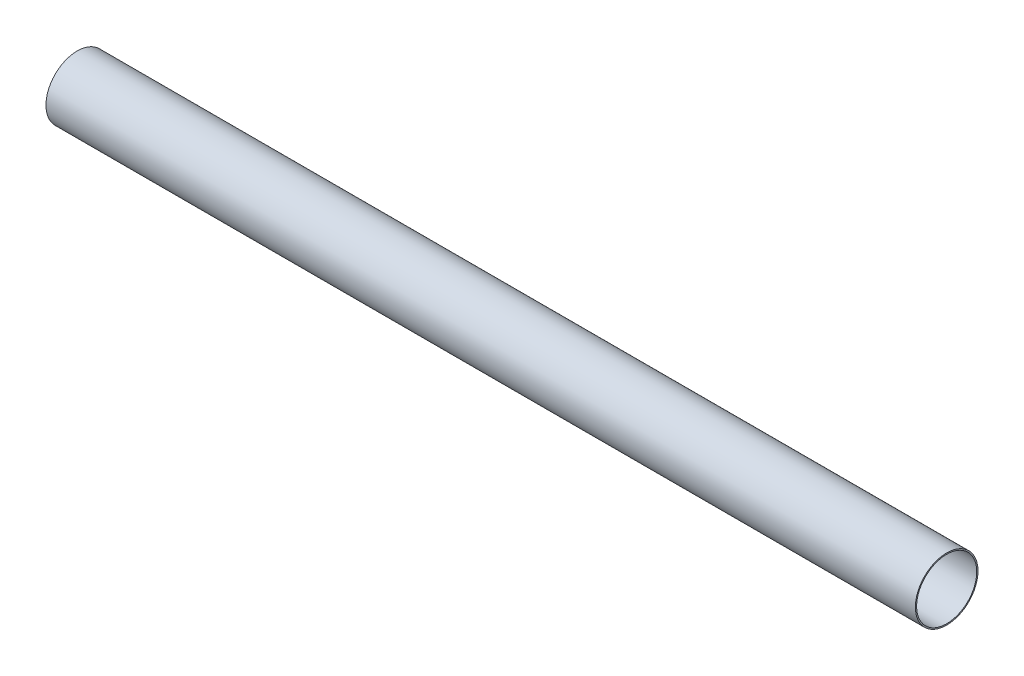
SolidWorks part; units mm, degrees
material "Carbon Fiber 34 MSI Test"
ref_plane "Front Plane" through (0, 0, 0) normal (0, 0, 1) x (1, 0, 0)
ref_plane "Top Plane" through (0, 0, 0) normal (0, 1, 0) x (1, 0, 0)
ref_plane "Right Plane" through (0, 0, 0) normal (1, 0, 0) x (0, 0, -1)
sketch "Sketch1" plane through (0, 0, 0) normal (0, 1, 0) x (1, 0, 0)
  line L0 (0, 0) -> (-69370.3028, 0) construction
  line L1 (0, 39.6875) -> (1101.725, 39.6875)
  line L2 (1101.725, 39.6875) -> (1101.725, 38.1)
  line L3 (1101.725, 38.1) -> (0, 38.1)
  line L4 (0, 38.1) -> (0, 39.6875)
  line L5 (0, 38.1) -> (0, 0) construction
  line L6 (-101.6, 19.05) -> (-101.6, 0) construction
  line L7 (0, 19.05) -> (-101.6, 19.05) construction
  line L8 (1101.725, 38.1) -> (1101.725, 0) construction
  line L9 (1101.725, 19.05) -> (1000.125, 19.05) construction
  line L10 (1000.125, 19.05) -> (1000.125, 0) construction
  dimension "D1" = 79.375
  dimension "D2" = 76.2
  dimension "D3" = 1101.725
  dimension "D4" = 101.6
revolve "Revolve1" add sketch "Sketch1" angle 360 about L0
